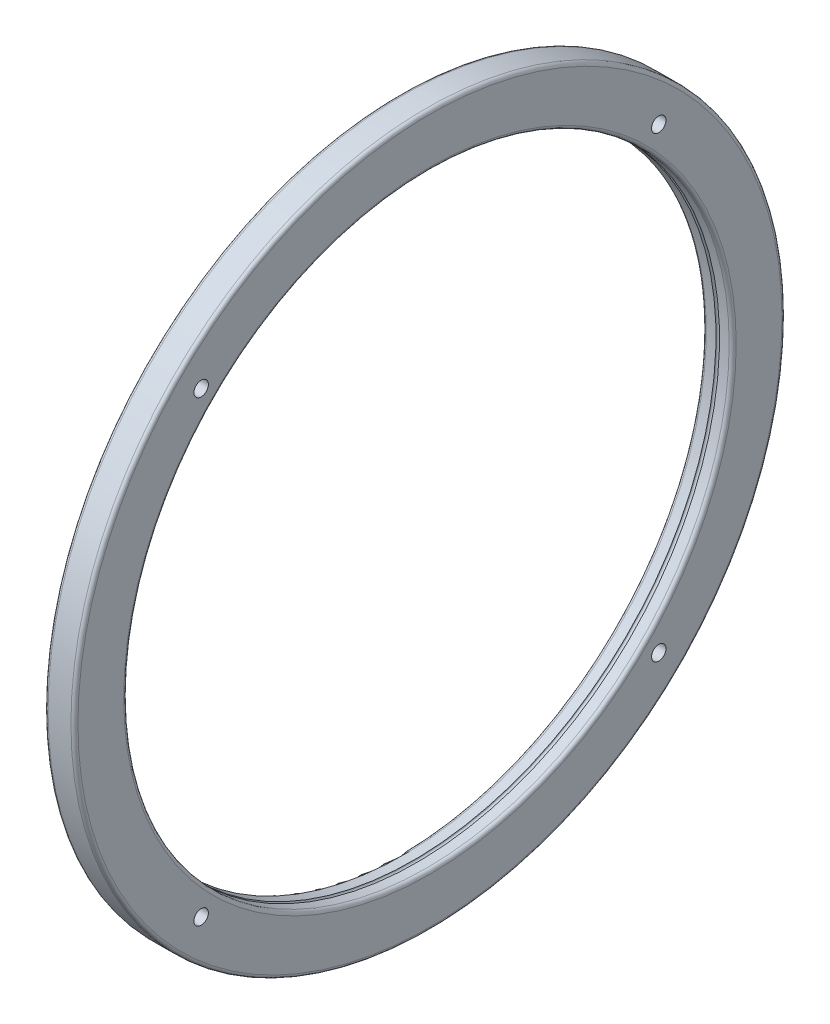
SolidWorks part; units mm, degrees
ref_plane "Front Plane" through (0, 0, 0) normal (0, 0, 1) x (1, 0, 0)
ref_plane "Top Plane" through (0, 0, 0) normal (0, 1, 0) x (1, 0, 0)
ref_plane "Right Plane" through (0, 0, 0) normal (1, 0, 0) x (0, 0, -1)
sketch "Sketch1" plane through (0, 0, 0) normal (0, 1, 0) x (1, 0, 0)
  line L0 (0, 0) -> (0, 101) construction
  line L1 (-4.25, 101) -> (4.25, 101)
  line L2 (4.25, 101) -> (4.25, 86)
  line L4 (-4.25, 86) -> (-4.25, 101)
  line L6 (-4.25, 86) -> (-0.4984, 86)
  line L7 (-0.0016, 86) -> (0.0016, 86)
  line L8 (0.5016, 86) -> (4.25, 86)
  arc A2 (-0.0016, 86) -> (0.0016, 86) centre (0, 8.9505) cw
  arc A3 (0.5016, 86) -> (-0.4984, 86) centre (0.0016, 86) ccw
  point P11 (0, 101)
  dimension "D3" = 86
  dimension "D5" = 0.5032
  dimension "D4" = 1
  dimension "D1" = 8.5
  dimension "D2" = 15
sketch "Sketch2" plane through (0, 0, 0) normal (0, 0, 1) x (1, 0, 0)
  line L0 (0, 0) -> (4.25, 0) construction
  line L1 (-4.25, 0) -> (-0.4984, 0) construction
  line L2 (-4.25, 0) -> (4.25, 0) construction
revolve "Revolve1" add sketch "Sketch1" angle 360 about L0
fillet "Fillet1" radius 1 4 edges at (-4.25, 0, 86) (4.25, 0, 86) (4.25, 0, 101) (-4.25, 0, 101)
sketch "Sketch3" plane through (4.25, 0, 0) normal (1, 0, 0) x (0, 0, -1)
  line L0 (-101, 0) -> (101, 0) construction
  line L2 (-65, 65) -> (65, 65) construction
  line L3 (-65, 65) -> (-65, -65) construction
  line L4 (-65, -65) -> (65, -65) construction
  line L5 (65, 65) -> (65, -65) construction
  line L6 (-65, 65) -> (65, -65) construction
  line L7 (-65, -65) -> (65, 65) construction
  circle A1 centre (0, 0) radius 101 construction
  circle A2 centre (-65, -65) radius 2.05
  circle A5 centre (-65, 65) radius 2.05
  circle A7 centre (65, 65) radius 2.05
  circle A8 centre (65, -65) radius 2.05
  point P10 (0, 0)
  point P17 (15, 15)
  point P22 (0, 0)
  dimension "D1" = 4.1
  dimension "D2" = 4
  dimension "D6" = 130
  dimension "D7" = 130
extrude "Cut-Extrude1" cut sketch "Sketch3" against normal up to next
